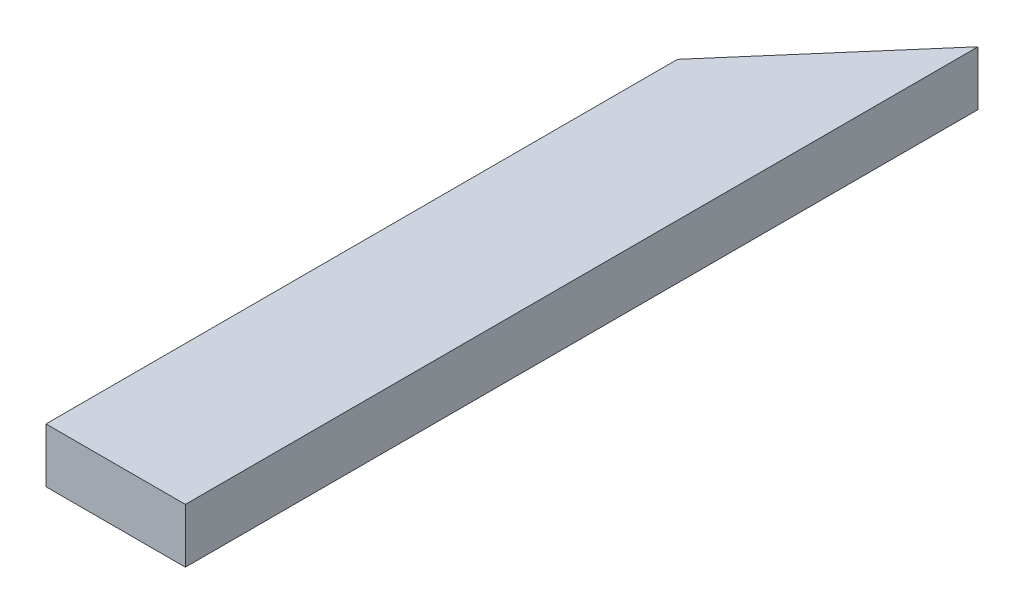
SolidWorks part; units mm, degrees
ref_plane "Front Plane" through (0, 0, 0) normal (0, 0, 1) x (1, 0, 0)
ref_plane "Top Plane" through (0, 0, 0) normal (0, 1, 0) x (1, 0, 0)
ref_plane "Right Plane" through (0, 0, 0) normal (1, 0, 0) x (0, 0, -1)
sketch "Sketch1" plane through (0, 0, 0) normal (0, 1, 0) x (1, 0, 0)
  line L0 (0, 0) -> (32.512, 0)
  line L1 (0, 0) -> (0, 147.32)
  line L2 (32.512, 0) -> (32.512, 184.912)
  line L3 (0, 147.32) -> (32.512, 184.912)
  dimension "D1" = 32.512
  dimension "D2" = 147.32
  dimension "D3" = 184.912
extrude "Boss-Extrude1" add sketch "Sketch1" along normal blind 12.7
